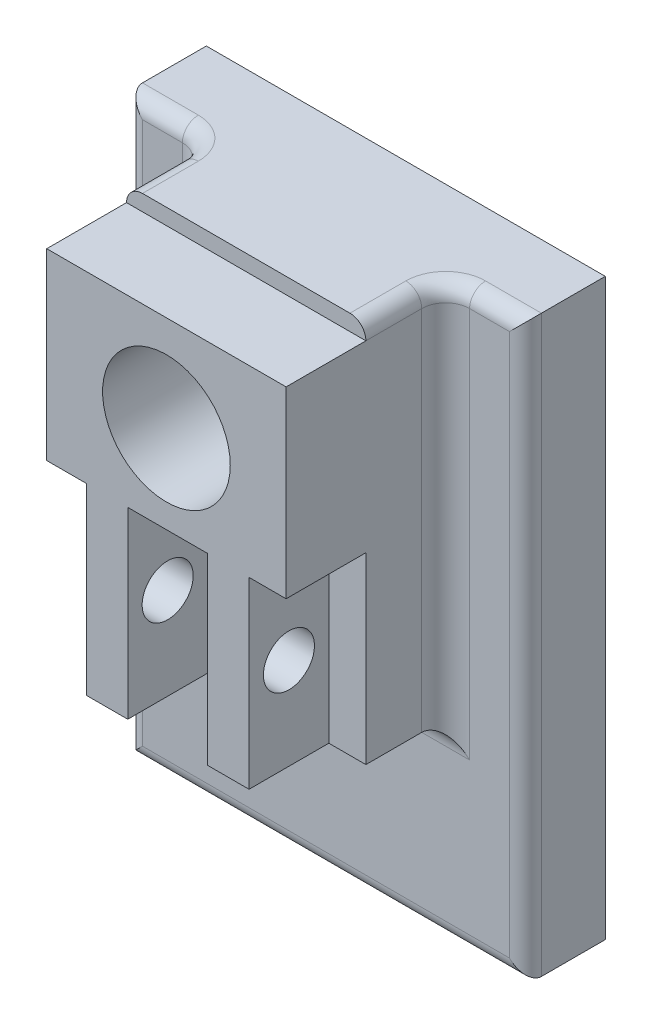
SolidWorks part; units mm, degrees
ref_plane "Front" through (0, 0, 0) normal (0, 0, 1) x (1, 0, 0)
ref_plane "Top" through (0, 0, 0) normal (0, 1, 0) x (1, 0, 0)
ref_plane "Right" through (0, 0, 0) normal (1, 0, 0) x (0, 0, -1)
sketch "Sketch1" plane through (0, 0, 0) normal (0, 0, 1) x (1, 0, 0)
  line L0 (-7.7947, 102.7128) -> (-7.7947, -77.2872) construction
  line L1 (-70.2947, 102.7128) -> (54.7053, 102.7128)
  line L2 (-70.2947, 102.7128) -> (-70.2947, -77.2872)
  line L3 (-70.2947, -77.2872) -> (54.7053, -77.2872)
  line L4 (54.7053, 102.7128) -> (54.7053, -77.2872)
  dimension "D1" = 180
  dimension "D2" = 125
extrude "Base-Extrude" add sketch "Sketch1" along normal blind 25
sketch "Sketch2" plane through (0, 0, 25) normal (0, 0, 1) x (1, 0, 0)
  line L0 (54.7053, 102.7128) -> (-70.2947, 102.7128) construction
  line L1 (-45.2947, 102.7128) -> (29.7053, 102.7128)
  line L2 (-45.2947, 102.7128) -> (-45.2947, -17.2872)
  line L3 (-45.2947, -17.2872) -> (29.7053, -17.2872)
  line L6 (29.7053, 102.7128) -> (29.7053, -17.2872)
  dimension "D1" = 25
  dimension "D2" = 25
  dimension "D3" = 120
extrude "Boss-Extrude1" add sketch "Sketch2" along normal blind 25
fillet "Fillet2" radius 7.5 3 edges at (-45.2947, 42.7128, 25) (-7.7947, -17.2872, 25) (29.7053, 42.7128, 25)
fillet "Fillet4" radius 5 9 edges at (54.7053, 12.7128, 25) (45.9553, 102.7128, 25) (-45.2947, 102.7128, 41.25) (29.7053, 102.7128, 41.25) (-61.5447, 102.7128, 25) (31.902, 102.7128, 27.1967) (-47.4914, 102.7128, 27.1967) (-70.2947, 12.7128, 25) (-7.7947, -77.2872, 25)
sketch "Sketch4" plane through (0, 0, 50) normal (0, 0, 1) x (1, 0, 0)
  line L0 (29.7053, -17.2872) -> (29.7053, 97.7128) construction
  line L1 (-45.2947, 97.7128) -> (-45.2947, -17.2872) construction
  line L3 (29.7053, 40.2128) -> (-45.2947, 40.2128)
  line L4 (29.7053, 40.2128) -> (29.7053, 97.7128)
  line L5 (29.7053, 97.7128) -> (-45.2947, 97.7128)
  line L6 (-45.2947, 40.2128) -> (-45.2947, 97.7128)
extrude "Boss-Extrude2" add sketch "Sketch4" along normal blind 25
sketch "Sketch5" [suppressed] plane through (0, 0, 50) normal (0, 0, 1) x (1, 0, 0)
  line L0 (-45.2947, 40.2128) -> (29.7053, 40.2128) construction
  line L1 (-32.7947, 40.2128) -> (-20.2947, 40.2128)
  line L2 (-32.7947, 40.2128) -> (-32.7947, 0.2128)
  line L3 (-32.7947, 0.2128) -> (-20.2947, 0.2128)
  line L4 (17.2053, 40.2128) -> (17.2053, 0.2128)
  line L5 (-45.2947, 40.2128) -> (-45.2947, -17.2872) construction
  line L6 (29.7053, -17.2872) -> (29.7053, 40.2128) construction
  line L7 (4.7053, 40.2128) -> (17.2053, 40.2128)
  line L8 (-45.2947, 40.2128) -> (29.7053, 40.2128) construction
  line L9 (-20.2947, 40.2128) -> (-20.2947, 0.2128)
  line L11 (4.7053, 40.2128) -> (4.7053, 0.2128)
  line L12 (4.7053, 0.2128) -> (17.2053, 0.2128)
  dimension "D1" = 12.5
  dimension "D2" = 12.5
  dimension "D3" = 12.5
  dimension "D4" = 12.5
  dimension "D5" = 40
extrude "Boss-Extrude3" [suppressed] add sketch "Sketch5" along normal up to vertex
sketch "Sketch6" [suppressed] plane through (-32.7947, 0, 0) normal (-1, 0, 0) x (0, 0, 1)
  line L0 (75, 0.2128) -> (50, 0.2128) construction
  line L1 (75, 40.2128) -> (75, 0.2128) construction
  circle A0 centre (62.5, 20.2128) radius 7.5
  dimension "D2" = 15
  dimension "D1" = 12.5
  dimension "D3" = 20
extrude "Cut-Extrude1" [suppressed] cut sketch "Sketch6" against normal blind 60
sketch "Sketch7" plane through (0, 0, 75) normal (0, 0, 1) x (1, 0, 0)
  line L2 (29.7053, 97.7128) -> (-45.2947, 97.7128) construction
  line L5 (54.7053, 102.7128) -> (54.7053, -77.2872) construction
  circle A0 centre (-7.7947, 67.7128) radius 20
  dimension "D3" = 40
  dimension "D1" = 62.5
  dimension "D2" = 30
extrude "Cut-Extrude2" cut sketch "Sketch7" against normal blind 105
fillet "Fillet8" [suppressed] radius 7.62
fillet "Fillet9" [suppressed] radius 2.5
fillet "Fillet10" [suppressed] radius 2.5
sketch "Sketch8" plane through (0, 0, 50) normal (0, 0, 1) x (1, 0, 0)
  line L6 (-45.2947, -17.2872) -> (29.7053, -17.2872) construction
  line L7 (5.0929, 40.2128) -> (18.0929, 40.2128)
  line L8 (5.0929, 40.2128) -> (5.0929, -17.2872)
  line L9 (5.0929, -17.2872) -> (18.0929, -17.2872)
  line L10 (18.0929, 40.2128) -> (18.0929, -17.2872)
  line L11 (-19.9071, 40.2128) -> (-32.9071, 40.2128)
  line L12 (-19.9071, 40.2128) -> (-19.9071, -17.2872)
  line L13 (-19.9071, -17.2872) -> (-32.9071, -17.2872)
  line L14 (-32.9071, 40.2128) -> (-32.9071, -17.2872)
  dimension "D1" = 25
  dimension "D2" = 13
  dimension "D3" = 13
extrude "Boss-Extrude4" add sketch "Sketch8" along normal blind 25 contours L12 L11 L14 L13 | L8 L7 L10 L9
sketch "Sketch9" plane through (-32.9071, 0, 0) normal (-1, 0, 0) x (0, 0, 1)
  circle A0 centre (62.5, 11.4628) radius 8
  dimension "D1" = 16
extrude "Cut-Extrude3" cut sketch "Sketch9" against normal blind 80
